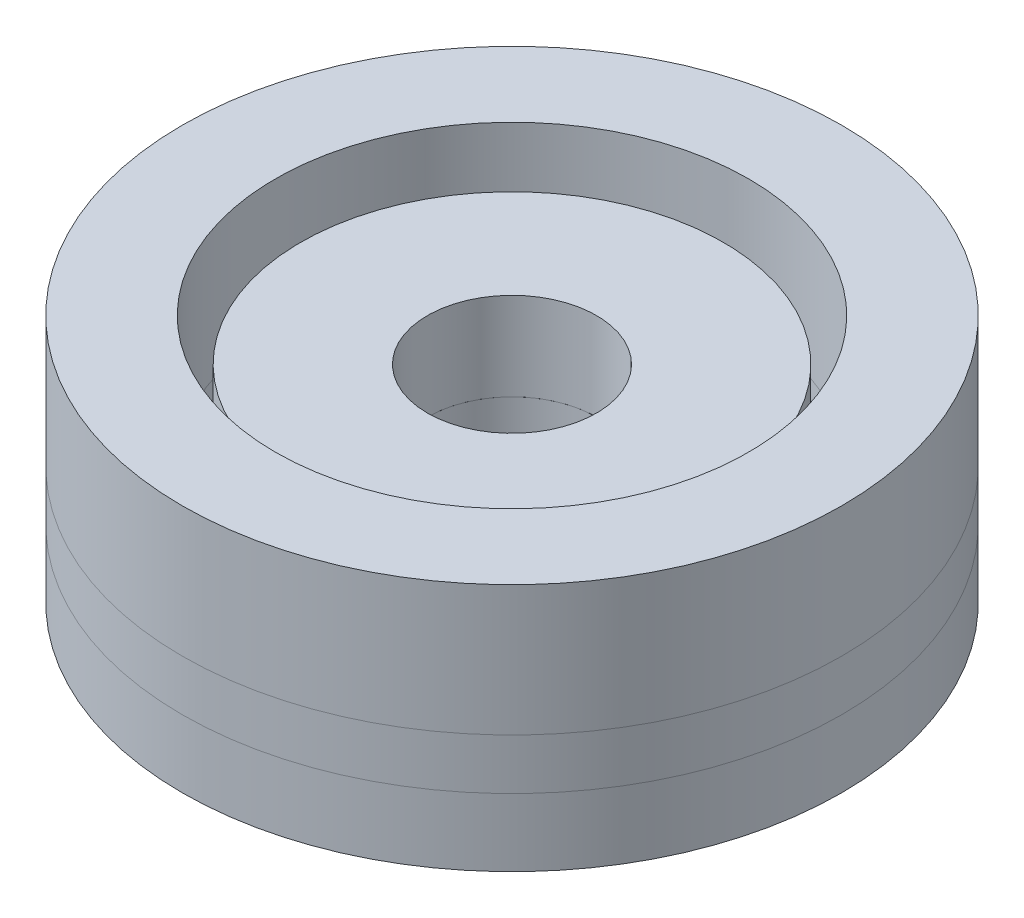
SolidWorks part; units mm, degrees
material "钨"
ref_plane "前视基准面" through (0, 0, 0) normal (0, 0, 1) x (1, 0, 0)
ref_plane "上视基准面" through (0, 0, 0) normal (0, 1, 0) x (1, 0, 0)
ref_plane "右视基准面" through (0, 0, 0) normal (1, 0, 0) x (0, 0, -1)
sketch "草图8" plane through (0, 0, 0) normal (0, 1, 0) x (1, 0, 0)
  circle A0 centre (514.9822, 0) radius 195
  circle A1 centre (514.9822, 0) radius 140
extrude "凸台-拉伸1" add sketch "草图8" against normal blind 77 separate body
sketch "草图10" plane through (0, -77, 0) normal (0, -1, 0) x (-1, 0, 0)
  circle A0 centre (-514.9822, 0) radius 195
  circle A1 centre (-514.9822, 0) radius 140
extrude "凸台-拉伸2" add sketch "草图10" along normal blind 30 separate body
sketch "草图11" plane through (0, -107, 0) normal (0, -1, 0) x (-1, 0, 0)
  circle A0 centre (-514.9822, 0) radius 195
  circle A1 centre (-514.9822, 0) radius 165
extrude "凸台-拉伸3" add sketch "草图11" along normal blind 40 separate body
ref_plane "基准面1" through (0, -25, 0) normal (0, 1, 0) x (1, 0, 0)
sketch "草图12" plane through (0, -25, 0) normal (0, 1, 0) x (1, 0, 0)
  circle A0 centre (514.9822, 0) radius 125
  circle A1 centre (514.9822, 0) radius 50
extrude "凸台-拉伸4" add sketch "草图12" against normal blind 52 separate body
sketch "草图17" plane through (0, -77, 0) normal (0, -1, 0) x (-1, 0, 0)
  circle A0 centre (-514.9822, 0) radius 50
  circle A1 centre (-514.9822, 0) radius 125
extrude "凸台-拉伸9" add sketch "草图17" along normal blind 30 separate body
sketch "草图18" plane through (0, -107, 0) normal (0, -1, 0) x (-1, 0, 0)
  circle A0 centre (-514.9822, 0) radius 50
  circle A1 centre (-514.9822, 0) radius 125
extrude "凸台-拉伸10" add sketch "草图18" along normal blind 70 separate body
equation "\"D1@凸台-拉伸1\"=\"P1\""
equation "\"D1@凸台-拉伸2\"=\"P3\""
equation "\"D1@凸台-拉伸3\"=\"P5\""
equation "\"D1@凸台-拉伸4\"=\"P2\""
equation "\"D1@凸台-拉伸9\"=\"P4\""
equation "\"D1@凸台-拉伸10\"=\"P6\""
equation "\"P1\"= 77'thickness1"
equation "\"P3\"= 30'thickness3"
equation "\"P5\"= 40'thickness5"
equation "\"P2\"= 52'thickness2"
equation "\"P4\"= 30'thickness4"
equation "\"P6\"= 70'thickness6"
